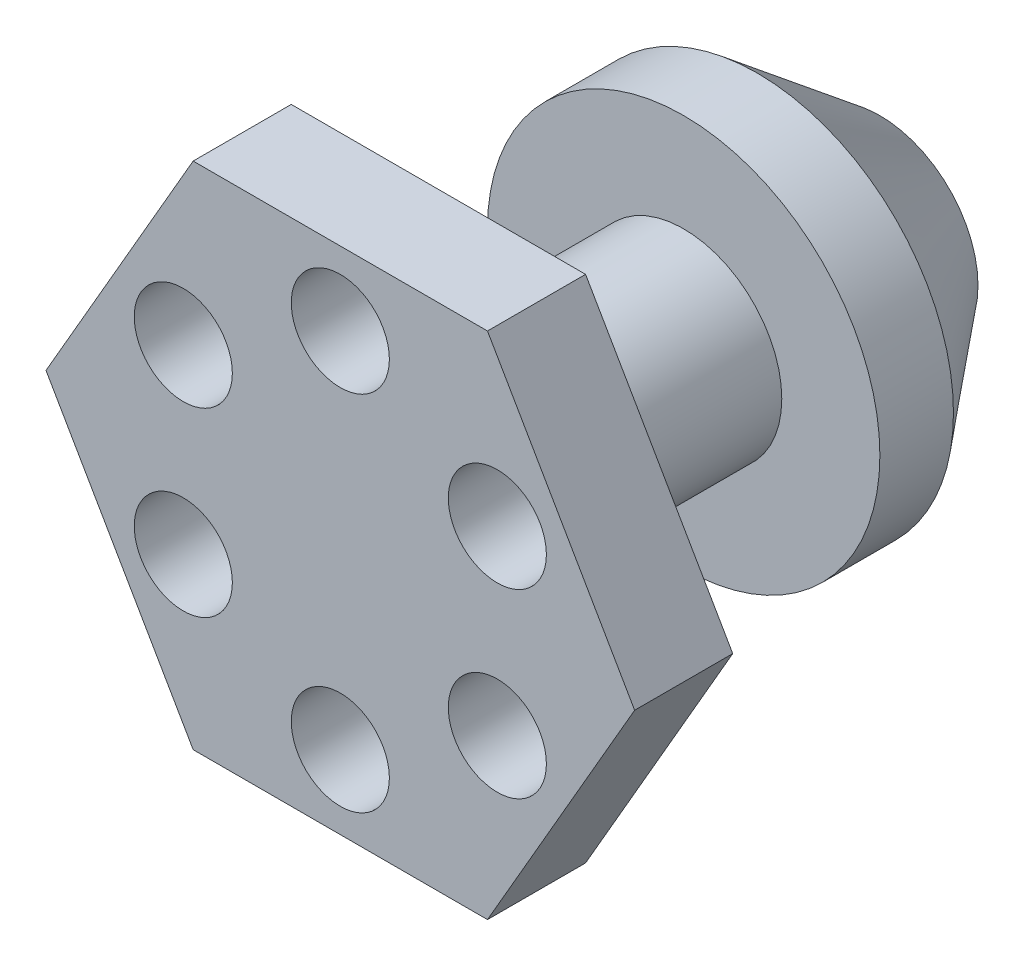
SolidWorks part; units mm, degrees
ref_plane "Front Plane" through (0, 0, 0) normal (0, 0, 1) x (1, 0, 0)
ref_plane "Top Plane" through (0, 0, 0) normal (0, 1, 0) x (1, 0, 0)
ref_plane "Right Plane" through (0, 0, 0) normal (1, 0, 0) x (0, 0, -1)
sketch "Sketch1" plane through (0, 0, 0) normal (0, 0, 1) x (1, 0, 0)
  line L0 (0, 0) -> (0, -46.9411) construction
  line L1 (-76.2, 0) -> (-38.1, -65.9911)
  line L2 (-38.1, -65.9911) -> (38.1, -65.9911)
  line L3 (38.1, -65.9911) -> (76.2, 0)
  line L4 (76.2, 0) -> (38.1, 65.9911)
  line L5 (38.1, 65.9911) -> (-38.1, 65.9911)
  line L6 (-38.1, 65.9911) -> (-76.2, 0)
  circle A0 centre (0, 0) radius 65.9911 construction
  circle A4 centre (0, -46.9411) radius 12.7
  circle A5 centre (-40.6522, -23.4706) radius 12.7
  circle A6 centre (-40.6522, 23.4706) radius 12.7
  circle A7 centre (0, 46.9411) radius 12.7
  circle A8 centre (40.6522, 23.4706) radius 12.7
  circle A9 centre (40.6522, -23.4706) radius 12.7
  dimension "D2" = 19.05
  dimension "D3" = 25.4
  dimension "D1" = 76.2
  dimension "D5" = 46.9411
  dimension "D4" = 6
extrude "Boss-Extrude3" add sketch "Sketch1" along normal blind 25.4
sketch "Sketch2" plane through (0, 0, 0) normal (0, 1, 0) x (1, 0, 0)
  line L0 (0, 33.1866) -> (0, 90.0378) construction
  line L1 (0, 0) -> (0, 114.3)
  line L2 (50.8, 82.55) -> (25.4, 114.3)
  line L3 (50.8, 82.55) -> (50.8, 63.5)
  line L4 (50.8, 63.5) -> (25.4, 63.5)
  line L5 (25.4, 63.5) -> (25.4, 0)
  line L6 (38.1, 0) -> (-38.1, 0) construction
  line L7 (38.1, -25.4) -> (-38.1, -25.4) construction
  line L9 (0, 114.3) -> (25.4, 114.3)
  dimension "D1" = 88.9
  dimension "D2" = 107.95
  dimension "D3" = 139.7
  dimension "D4" = 25.4
  dimension "D5" = 50.8
  dimension "D6" = 25.4
revolve "Revolve-Thin1" add sketch "Sketch2" angle 360 about L0
